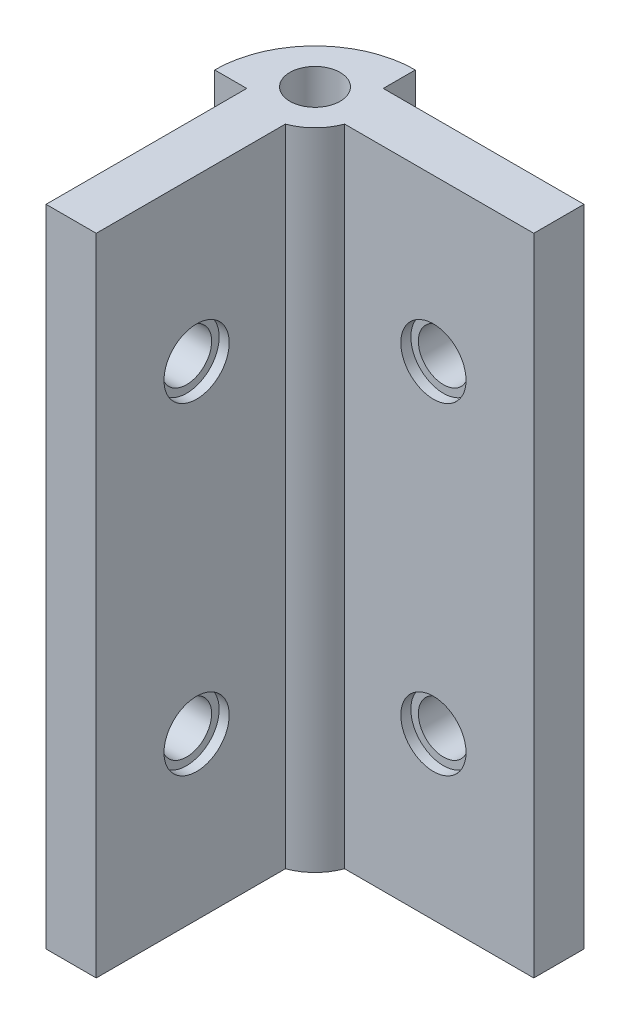
SolidWorks part; units mm, degrees
material "ABS"
ref_plane "Front Plane" through (0, 0, 0) normal (0, 0, 1) x (1, 0, 0)
ref_plane "Top Plane" through (0, 0, 0) normal (0, 1, 0) x (1, 0, 0)
ref_plane "Right Plane" through (0, 0, 0) normal (1, 0, 0) x (0, 0, -1)
sketch "Sketch4" plane through (0, 0, 0) normal (0, 1, 0) x (1, 0, 0)
  line L1 (-16.4403, 12.5012) -> (-16.4403, -277.4988) construction
  line L12 (-5.2868, 14.3012) -> (13.5597, 14.3012)
  line L35 (-8.2403, 11.3476) -> (-8.2403, -7.4988)
  line L36 (148.5597, 22.5012) -> (-6.4403, 22.5012) construction
  line L42 (-16.4403, 22.5012) -> (-13.5114, 19.5722) construction
  line L44 (-16.4403, 12.5012) -> (-13.2403, 12.5012)
  line L45 (-13.2403, 12.5012) -> (-13.2403, -7.4988)
  line L46 (-13.2403, -7.4988) -> (-8.2403, -7.4988)
  line L47 (-13.5114, 19.5722) -> (-11.7436, 17.8045) construction
  line L49 (-11.7436, 17.8045) -> (-9.9759, 16.0367) construction
  line L51 (-6.4403, 22.5012) -> (-6.4403, 19.3012)
  line L52 (-6.4403, 19.3012) -> (13.5597, 19.3012)
  line L53 (13.5597, 19.3012) -> (13.5597, 14.3012)
  line L54 (-6.2403, 19.5012) -> (148.3597, 19.5012) construction
  line L55 (-9.9759, 16.0367) -> (-8.2081, 14.2689) construction
  line L56 (-8.2081, 14.2689) -> (-6.4403, 12.5012) construction
  line L60 (-16.4403, 22.5012) -> (-16.4403, 12.5012) construction
  line L61 (-16.4403, 22.5012) -> (-6.4403, 22.5012) construction
  line L62 (-9.9759, 16.0367) -> (-4.9759, 16.0367) construction
  line L63 (-9.9759, 11.0367) -> (-9.9759, 16.0367) construction
  arc A2 (-6.4403, 22.5012) -> (-16.4403, 12.5012) centre (-6.4403, 12.5012) ccw
  circle A8 centre (-9.9759, 16.0367) radius 2.5
  arc A13 (-4.9759, 16.0367) -> (-9.9759, 11.0367) centre (-9.9759, 16.0367) cw construction
  arc A16 (-5.2868, 14.3012) -> (-8.2403, 11.3476) centre (-9.9759, 16.0367) cw
  arc A17 (-6.4403, 22.5012) -> (-16.4403, 12.5012) centre (-6.4403, 12.5012) ccw construction
  dimension "D6" = 2.5
  dimension "D7" = 5
  dimension "D1" = 5
  dimension "D5" = 0.2
  dimension "D8" = 20
  dimension "D9" = 2.5
extrude "Boss-Extrude1" add sketch "Sketch4" along normal blind 64.27
sketch "Sketch5" plane through (0, 0, -19.3012) normal (0, 0, -1) x (-1, 0, 0)
  line L0 (6.4403, 64.27) -> (-13.5597, 64.27) construction
  line L1 (-3.5597, 64.27) -> (-3.5597, 48.2025) construction
  line L2 (-3.5597, 48.2025) -> (-3.5597, 32.135) construction
  line L3 (-3.5597, 32.135) -> (-3.5597, 16.0675) construction
  line L4 (-3.5597, 16.0675) -> (-3.5597, 0) construction
  line L5 (-13.5597, 0) -> (6.4403, 0) construction
  circle A10 centre (-3.5597, 48.2025) radius 2.5
  circle A12 centre (-3.5597, 16.0675) radius 2.5
  point P2 (-3.5597, 64.27)
  dimension "D1" = 5
extrude "Cut-Extrude1" cut sketch "Sketch5" against normal through all
sketch "Sketch6" plane through (-13.2403, 0, 0) normal (-1, 0, 0) x (0, 0, 1)
  line L0 (7.4988, 64.27) -> (-12.5012, 64.27) construction
  line L1 (-2.5012, 64.27) -> (-2.5012, 48.2025) construction
  line L2 (-2.5012, 16.0675) -> (-2.5012, 32.135) construction
  line L3 (-2.5012, 16.0675) -> (-2.5012, 0) construction
  line L4 (-12.5012, 0) -> (7.4988, 0) construction
  line L5 (-2.5012, 32.135) -> (-2.5012, 48.2025) construction
  circle A0 centre (-2.5012, 48.2025) radius 2.5
  circle A2 centre (-2.5012, 16.0675) radius 2.5
  point P2 (-2.5012, 64.27)
  dimension "D1" = 5
extrude "Cut-Extrude2" cut sketch "Sketch6" against normal through all
sketch "Sketch7" plane through (-8.2403, 0, 0) normal (1, 0, 0) x (0, 0, -1)
  circle A0 centre (2.5012, 48.2025) radius 3.25
  circle A1 centre (2.5012, 16.0675) radius 3.25
  circle A2 centre (2.5012, 48.2025) radius 2.5 construction
  circle A3 centre (2.5012, 16.0675) radius 2.5 construction
  dimension "D1" = 6.5
extrude "Cut-Extrude3" cut sketch "Sketch7" against normal blind 1
sketch "Sketch8" plane through (0, 0, -14.3012) normal (0, 0, 1) x (1, 0, 0)
  circle A0 centre (3.5597, 48.2025) radius 3.25
  circle A1 centre (3.5597, 16.0675) radius 3.25
  circle A2 centre (3.5597, 48.2025) radius 2.5 construction
  circle A3 centre (3.5597, 16.0675) radius 2.5 construction
  dimension "D1" = 6.5
extrude "Cut-Extrude4" cut sketch "Sketch8" against normal blind 1
equation "\"tolerance\"= 0.1mm"
